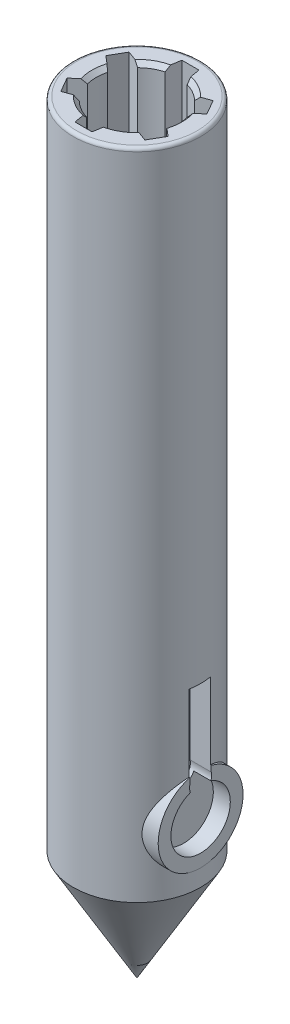
SolidWorks part; units mm, degrees
material "ABS"
ref_plane "Front" through (0, 0, 0) normal (0, 0, 1) x (1, 0, 0)
ref_plane "Top" through (0, 0, 0) normal (0, 1, 0) x (1, 0, 0)
ref_plane "Right" through (0, 0, 0) normal (1, 0, 0) x (0, 0, -1)
sketch "Sketch1" plane through (0, 0, 0) normal (1, 0, 0) x (0, 0, -1)
  line L0 (-6.096, 38.1) -> (-6.096, 8.706)
  line L1 (-6.096, 8.706) -> (0, 0)
  line L2 (0, 0) -> (0, 26.3018) construction
  line L3 (-6.096, 38.1) -> (-9.525, 38.1)
  line L4 (-9.525, 38.1) -> (-9.525, -59.7022)
  line L5 (-9.525, -59.7022) -> (0, -76.2)
  line L6 (0, -76.2) -> (0, 0)
  dimension "D1" = 35
  dimension "D2" = 12.192
  dimension "D3" = 30
  dimension "D4" = 19.05
  dimension "D5" = 38.1
  dimension "D6" = 76.2
revolve "mainBody" add sketch "Sketch1" angle 360 about L2
ref_plane "Tangent" through (9.525, 0, 0) normal (1, 0, 0) x (0, 0, -1)
sketch "sensor" plane through (9.525, 0, 0) normal (1, 0, 0) x (0, 0, -1)
  line L1 (0, -57.1622) -> (0, -59.7022) construction
  line L2 (9.525, -59.7022) -> (-9.525, -59.7022) construction
  circle A0 centre (0, -50.8122) radius 6.35
  dimension "D1" = 12.7
  dimension "D2" = 2.54
extrude "Boss-Extrude1" add sketch "sensor" against normal up to surface (2.4255 mm away)
chamfer "Chamfer1" distance 0.635 angle 45 1 edges at (0, 38.1, -6.096)
fillet "Fillet3" radius 0.508 1 edges at (0, 38.1, -9.525)
sketch "Sketch4" plane through (9.525, 0, 0) normal (1, 0, 0) x (0, 0, -1)
  circle A0 centre (0, -50.8122) radius 4.445
  dimension "D1" = 8.89
extrude "Cut-Extrude1" cut sketch "Sketch4" against normal blind 2.54
sketch "Sketch5" plane through (9.525, 0, 0) normal (1, 0, 0) x (0, 0, -1)
  line L1 (-1.5875, -33.2862) -> (1.5875, -33.2862)
  line L2 (-1.5875, -33.2862) -> (-1.5875, -45.5327)
  line L3 (-1.5875, -45.9862) -> (1.5875, -45.9862) construction
  line L4 (1.5875, -33.2862) -> (1.5875, -45.5327)
  line L5 (-1.5875, -33.2862) -> (1.5875, -45.9862) construction
  line L6 (-1.5875, -45.9862) -> (1.5875, -33.2862) construction
  arc A0 (-1.5875, -45.5327) -> (1.5875, -45.5327) centre (0, -45.9862) ccw
  point P2 (0, -39.6362)
  dimension "D1" = 3.302
  dimension "D2" = 4.826
  dimension "D3" = 3.175
  dimension "D4" = 12.7
extrude "Cut-Extrude2" cut sketch "Sketch5" against normal offset from surface (3.175 mm away) 0.635 up to face at (6.985, -50.8122, -4.445) offset beyond the face yes
sketch "Sketch13" plane through (0, 38.1, 0) normal (0, 1, 0) x (1, 0, 0)
  line L0 (-1.27, 8.001) -> (1.27, 8.001)
  line L1 (1.27, 8.001) -> (2.2759, 2.2963)
  line L2 (2.2759, 2.2963) -> (-2.2759, 2.2963)
  line L3 (-2.2759, 2.2963) -> (-1.27, 8.001)
  line L5 (0, 8.001) -> (0, 2.2963) construction
  circle A0 centre (0, 0) radius 6.731 construction
  point P5 (0, 6.731)
  dimension "D2" = 2.54
  dimension "D3" = 80
  dimension "D4" = 1.27
extrude "Cut-Extrude8" cut sketch "Sketch13" against normal up to surface (33.4827 mm away)
pattern_circular "CirPattern1" count 6 over 360 about axis through (0, 0, 0) along (0, 1, 0) of "Cut-Extrude8"
sketch "Sketch14" plane through (0, 0, 0) normal (0, 0, 1) x (1, 0, 0)
  line L0 (0, -3.81) -> (7.9375, -3.81)
  line L1 (7.9375, -3.81) -> (7.9375, -19.6977)
  line L2 (7.9375, -19.6977) -> (3.175, -19.6977)
  line L3 (3.175, -19.6977) -> (3.175, -22.7457)
  line L4 (3.175, -22.7457) -> (7.9375, -22.7457)
  line L5 (7.9375, -22.7457) -> (7.9375, -32.2707)
  line L6 (7.9375, -32.2707) -> (0, -32.2707)
  line L7 (0, -32.2707) -> (0, -3.81)
  line L8 (0, 0) -> (0, 5.4381) construction
  dimension "D1" = 3.81
  dimension "D2" = 15.875
  dimension "D3" = 15.8877
  dimension "D4" = 6.35
  dimension "D5" = 15.875
  dimension "D6" = 9.525
  dimension "D7" = 3.048
revolve "Cut-Revolve4" cut sketch "Sketch14" angle 360 about L8
